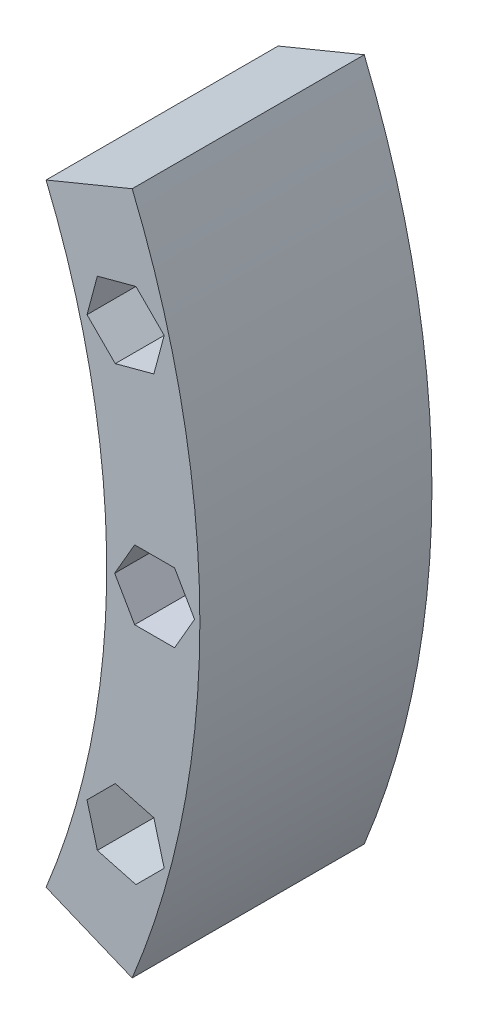
SolidWorks part; units mm, degrees
ref_plane "Front Plane" through (0, 0, 0) normal (0, 0, 1) x (1, 0, 0)
ref_plane "Top Plane" through (0, 0, 0) normal (0, 1, 0) x (1, 0, 0)
ref_plane "Right Plane" through (0, 0, 0) normal (1, 0, 0) x (0, 0, -1)
sketch "Sketch1" plane through (0, 0, 0) normal (0, 0, 1) x (1, 0, 0)
  line L0 (0, 0) -> (197.1113, 0) construction
  line L1 (76.2472, 0) -> (78.1236, -3.25)
  line L2 (77.1996, -31.8194) -> (69.8032, -28.7708)
  line L3 (77.1996, 31.8194) -> (69.8032, 28.7708)
  line L4 (76.5269, 17.9171) -> (74.4857, 19.9584) construction
  line L5 (77.1132, 0) -> (78.5566, -2.5) construction
  line L6 (78.5566, -2.5) -> (81.4434, -2.5) construction
  line L7 (81.4434, -2.5) -> (82.8868, 0) construction
  line L8 (82.8868, 0) -> (81.4434, 2.5) construction
  line L9 (81.4434, 2.5) -> (78.5566, 2.5) construction
  line L10 (78.5566, 2.5) -> (77.1132, 0) construction
  line L11 (74.4857, -19.9584) -> (75.2328, -22.7468) construction
  line L12 (75.2328, -22.7468) -> (78.0212, -23.4939) construction
  line L13 (78.0212, -23.4939) -> (80.0625, -21.4527) construction
  line L14 (80.0625, -21.4527) -> (79.3153, -18.6643) construction
  line L15 (79.3153, -18.6643) -> (76.5269, -17.9171) construction
  line L16 (76.5269, -17.9171) -> (74.4857, -19.9584) construction
  line L17 (79.3153, 18.6643) -> (76.5269, 17.9171) construction
  line L18 (80.0625, 21.4527) -> (79.3153, 18.6643) construction
  line L19 (78.0212, 23.4939) -> (80.0625, 21.4527) construction
  line L20 (75.2328, 22.7468) -> (78.0212, 23.4939) construction
  line L21 (74.4857, 19.9584) -> (75.2328, 22.7468) construction
  line L22 (78.1236, -3.25) -> (81.8764, -3.25)
  line L23 (81.8764, -3.25) -> (83.7528, 0)
  line L24 (83.7528, 0) -> (81.8764, 3.25)
  line L25 (81.8764, 3.25) -> (78.1236, 3.25)
  line L26 (78.1236, 3.25) -> (76.2472, 0)
  line L27 (79.9277, 18.0519) -> (76.3028, 17.0806)
  line L28 (76.3028, 17.0806) -> (73.6492, 19.7342)
  line L29 (73.6492, 19.7342) -> (74.6205, 23.3591)
  line L30 (74.6205, 23.3591) -> (78.2454, 24.3304)
  line L31 (78.2454, 24.3304) -> (80.899, 21.6768)
  line L32 (80.899, 21.6768) -> (79.9277, 18.0519)
  line L33 (74.6205, -23.3591) -> (78.2454, -24.3304)
  line L34 (78.2454, -24.3304) -> (80.899, -21.6768)
  line L35 (80.899, -21.6768) -> (79.9277, -18.0519)
  line L36 (79.9277, -18.0519) -> (76.3028, -17.0806)
  line L37 (76.3028, -17.0806) -> (73.6492, -19.7342)
  line L38 (73.6492, -19.7342) -> (74.6205, -23.3591)
  line L39 (77.1996, -31.8194) -> (77.893, -32.1052)
  line L40 (77.1996, 31.8194) -> (77.893, 32.1052)
  arc A0 (83.4988, 0.4398) -> (83.5, 0) centre (0, 0) cw construction
  arc A1 (69.8032, 28.7708) -> (69.8032, -28.7708) centre (0, 0) cw
  circle A2 centre (0, 0) radius 75.5 construction
  circle A3 centre (80, 0) radius 2.5 construction
  circle A4 centre (77.2741, -20.7055) radius 2.5 construction
  arc A5 (77.893, 32.1052) -> (77.893, -32.1052) centre (0, 0) cw
  arc A6 (77.1996, 31.8194) -> (80.5399, 22.0359) centre (0, 0) cw construction
  arc A7 (77.1996, 31.8194) -> (77.1996, -31.8194) centre (0, 0) cw construction
  arc A8 (83.4988, -0.4398) -> (80.7675, -21.1862) centre (0, 0) cw construction
  arc A9 (80.5399, -22.0359) -> (77.1996, -31.8194) centre (0, 0) cw construction
  arc A10 (80.5399, 22.0359) -> (80.7675, 21.1862) centre (0, 0) cw construction
  arc A11 (80.7675, 21.1862) -> (83.4988, 0.4398) centre (0, 0) cw construction
  arc A12 (83.5, 0) -> (83.4988, -0.4398) centre (0, 0) cw construction
  arc A13 (80.7675, -21.1862) -> (80.5399, -22.0359) centre (0, 0) cw construction
  dimension "D1" = 8
  dimension "D2" = 44.8
  dimension "D3" = 15
  dimension "D4" = 5
  dimension "D5" = 5
  dimension "D6" = 0.75
  dimension "D7" = 0.75
extrude "Boss-Extrude1" add sketch "Sketch1" along normal blind 21.8 from offset 0.01
